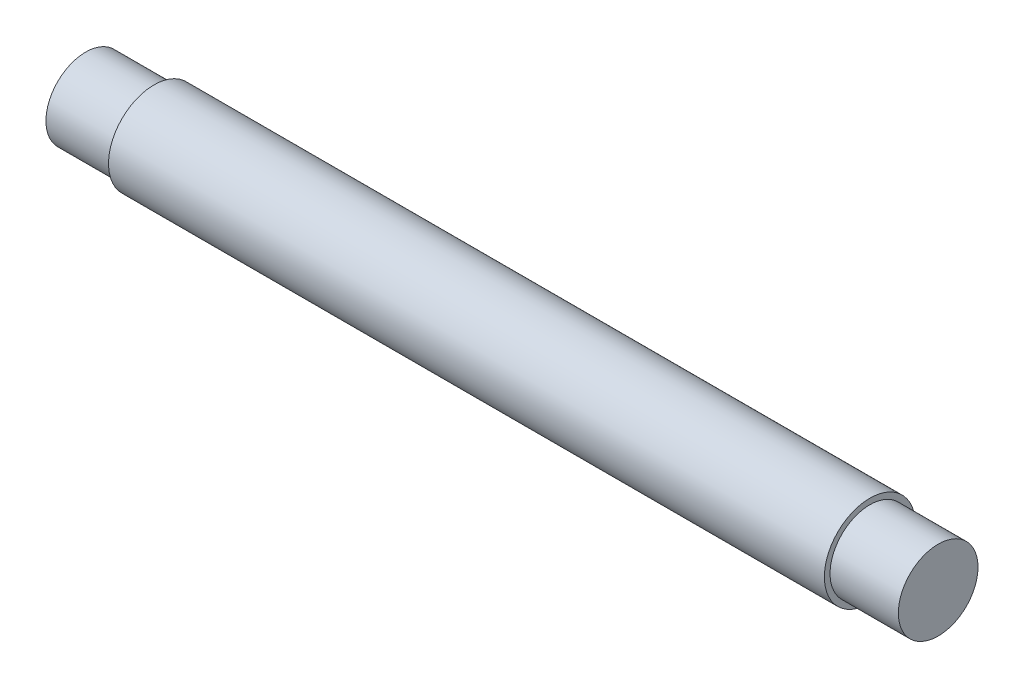
SolidWorks part; units mm, degrees
material "Cast Alloy Steel"
ref_plane "Front Plane" through (0, 0, 0) normal (0, 0, 1) x (1, 0, 0)
ref_plane "Top Plane" through (0, 0, 0) normal (0, 1, 0) x (1, 0, 0)
ref_plane "Right Plane" through (0, 0, 0) normal (1, 0, 0) x (0, 0, -1)
sketch "Sketch1" plane through (0, 0, 0) normal (0, 1, 0) x (1, 0, 0)
  line L0 (-187.25, 0) -> (-187.25, 17.5)
  line L1 (-187.25, 17.5) -> (-157.25, 17.5)
  line L2 (-157.25, 17.5) -> (-157.25, 20)
  line L3 (-157.25, 20) -> (157.25, 20)
  line L4 (157.25, 20) -> (157.25, 17.5)
  line L5 (157.25, 17.5) -> (187.25, 17.5)
  line L6 (187.25, 17.5) -> (187.25, 0)
  line L7 (187.25, 0) -> (-187.25, 0)
  line L8 (-22, 0) -> (22, 0) construction
  point P10 (0, 20)
  dimension "D1" = 314.5
  dimension "D2" = 30
  dimension "D3" = 20
  dimension "D4" = 17.5
revolve "Revolve1" add sketch "Sketch1" angle 360 about L7
